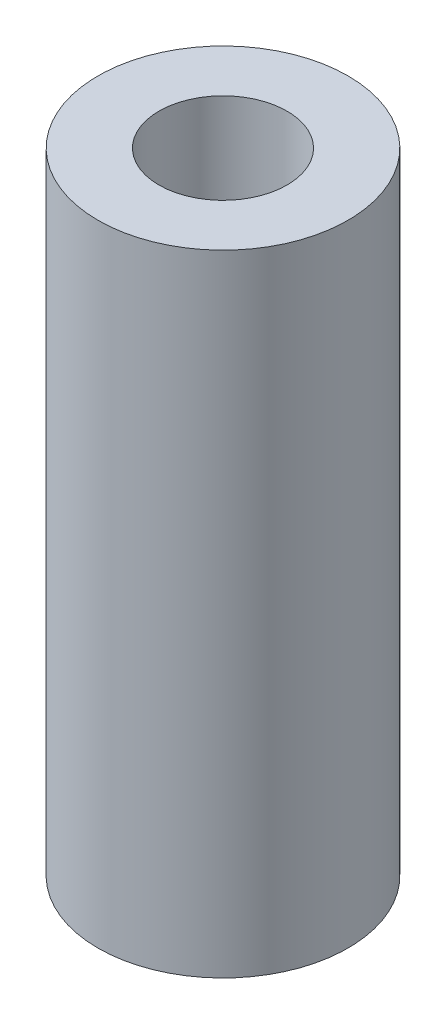
SolidWorks part; units mm, degrees
ref_plane "Front Plane" through (0, 0, 0) normal (0, 0, 1) x (1, 0, 0)
ref_plane "Top Plane" through (0, 0, 0) normal (0, 1, 0) x (1, 0, 0)
ref_plane "Right Plane" through (0, 0, 0) normal (1, 0, 0) x (0, 0, -1)
sketch "Sketch1" plane through (0, 0, 0) normal (0, 1, 0) x (1, 0, 0)
  circle A0 centre (0, 0) radius 1.575
  circle A1 centre (0, 0) radius 3.075
  dimension "D1" = 3.15
  dimension "D2" = 6.15
extrude "Boss-Extrude1" add sketch "Sketch1" along normal blind 15.5
